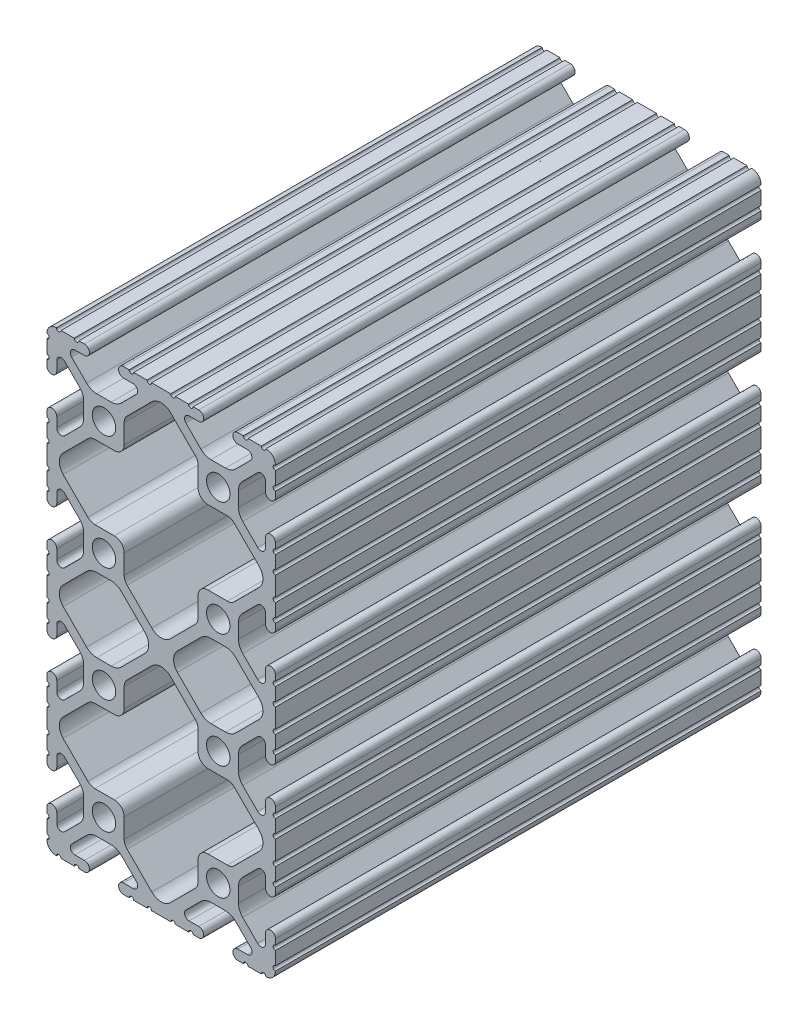
SolidWorks part; units mm, degrees
ref_plane "Front Plane" through (0, 0, 0) normal (0, 0, 1) x (1, 0, 0)
ref_plane "Top Plane" through (0, 0, 0) normal (0, 1, 0) x (1, 0, 0)
ref_plane "Right Plane" through (0, 0, 0) normal (1, 0, 0) x (0, 0, -1)
sketch "Sketch1" plane through (0, 0, 0) normal (0, 0, 1) x (1, 0, 0)
  line L0 (2.286, 55.2958) -> (-2.0184, 55.2958)
  line L1 (-3.5809, 55.943) -> (-9.0725, 61.4345)
  line L2 (-9.0725, 65.5655) -> (-3.5809, 71.057)
  line L3 (-2.0184, 71.7042) -> (2.286, 71.7042)
  line L4 (4.4958, 73.914) -> (4.4958, 78.2184)
  line L5 (5.143, 79.7809) -> (10.6345, 85.2725)
  line L6 (14.7655, 85.2725) -> (20.257, 79.7809)
  line L7 (20.9042, 78.2184) -> (20.9042, 73.914)
  line L8 (23.114, 71.7042) -> (27.4184, 71.7042)
  line L9 (28.9809, 71.057) -> (34.4725, 65.5655)
  line L10 (34.4725, 61.4345) -> (28.9809, 55.943)
  line L11 (27.4184, 55.2958) -> (23.114, 55.2958)
  line L12 (20.9042, 53.086) -> (20.9042, 48.7816)
  line L13 (20.257, 47.2191) -> (14.7655, 41.7275)
  line L14 (10.6345, 41.7275) -> (5.143, 47.2191)
  line L15 (4.4958, 48.7816) -> (4.4958, 53.086)
  line L16 (4.4958, 23.114) -> (4.4958, 27.4184)
  line L17 (5.143, 28.9809) -> (10.6345, 34.4725)
  line L18 (14.7655, 34.4725) -> (20.257, 28.9809)
  line L19 (20.9042, 27.4184) -> (20.9042, 23.114)
  line L20 (23.114, 20.9042) -> (27.4184, 20.9042)
  line L21 (28.9809, 20.257) -> (34.4725, 14.7655)
  line L22 (34.4725, 10.6345) -> (28.9809, 5.143)
  line L23 (27.4184, 4.4958) -> (23.114, 4.4958)
  line L24 (20.9042, 2.286) -> (20.9042, -2.0184)
  line L25 (20.257, -3.5809) -> (14.7655, -9.0725)
  line L26 (10.6345, -9.0725) -> (5.143, -3.5809)
  line L27 (4.4958, -2.0184) -> (4.4958, 2.286)
  line L28 (2.286, 4.4958) -> (-2.0184, 4.4958)
  line L29 (-3.5809, 5.143) -> (-9.0725, 10.6345)
  line L30 (-9.0725, 14.7655) -> (-3.5809, 20.257)
  line L31 (-2.0184, 20.9042) -> (2.286, 20.9042)
  line L32 (27.0186, 29.8958) -> (23.7824, 29.8958)
  line L33 (21.5373, 30.8258) -> (16.3286, 36.0346)
  line L34 (16.3286, 40.1654) -> (21.5373, 45.3742)
  line L35 (23.7824, 46.3042) -> (27.0186, 46.3042)
  line L36 (29.2636, 45.3743) -> (34.4725, 40.1655)
  line L37 (34.4725, 36.0345) -> (29.2636, 30.8257)
  line L38 (1.6176, 29.8958) -> (-1.6186, 29.8958)
  line L39 (-3.8636, 30.8257) -> (-9.0725, 36.0345)
  line L40 (-9.0725, 40.1655) -> (-3.8636, 45.3743)
  line L41 (-1.6186, 46.3042) -> (1.6176, 46.3042)
  line L42 (3.8627, 45.3742) -> (9.0714, 40.1654)
  line L43 (9.0714, 36.0346) -> (3.8627, 30.8258)
  line L44 (-12.7, 40.2336) -> (-12.7, 35.9664)
  line L45 (-12.7, 34.9504) -> (-12.7, 32.004)
  line L46 (-12.7, 30.988) -> (-12.7, 29.7434)
  line L47 (-10.4902, 29.7434) -> (-10.4902, 31.8743)
  line L48 (-8.7558, 32.5927) -> (-5.4258, 29.2627)
  line L49 (-4.4958, 27.0176) -> (-4.4958, 23.7824)
  line L50 (-5.4258, 21.5373) -> (-8.7558, 18.2073)
  line L51 (-10.4902, 18.9257) -> (-10.4902, 21.0566)
  line L52 (-12.7, 21.0566) -> (-12.7, 19.812)
  line L53 (-12.7, 18.796) -> (-12.7, 15.8496)
  line L54 (-12.7, 14.8336) -> (-12.7, 10.5664)
  line L55 (-12.7, 9.5504) -> (-12.7, 6.604)
  line L56 (-12.7, 5.588) -> (-12.7, 4.3434)
  line L57 (-10.4902, 4.3434) -> (-10.4902, 6.4743)
  line L58 (-8.7558, 7.1927) -> (-5.4258, 3.8627)
  line L59 (-4.4958, 1.6176) -> (-4.4958, -1.6176)
  line L60 (-5.4258, -3.8627) -> (-8.7558, -7.1927)
  line L61 (-10.4902, -6.4743) -> (-10.4902, -4.3434)
  line L62 (-12.7, -4.3434) -> (-12.7, -5.588)
  line L63 (-12.7, -6.604) -> (-12.7, -9.5504)
  line L64 (-9.5504, -12.7) -> (-6.604, -12.7)
  line L65 (-5.588, -12.7) -> (-4.3434, -12.7)
  line L66 (-4.3434, -10.4902) -> (-6.4743, -10.4902)
  line L67 (-7.1927, -8.7558) -> (-3.8627, -5.4258)
  line L68 (-1.6176, -4.4958) -> (1.6176, -4.4958)
  line L69 (3.8627, -5.4258) -> (7.1927, -8.7558)
  line L70 (6.4743, -10.4902) -> (4.3434, -10.4902)
  line L71 (4.3434, -12.7) -> (5.588, -12.7)
  line L72 (6.604, -12.7) -> (9.5504, -12.7)
  line L73 (10.5664, -12.7) -> (14.8336, -12.7)
  line L74 (15.8496, -12.7) -> (18.796, -12.7)
  line L75 (19.812, -12.7) -> (21.0566, -12.7)
  line L76 (21.0566, -10.4902) -> (18.9257, -10.4902)
  line L77 (18.2073, -8.7558) -> (21.5373, -5.4258)
  line L78 (23.7824, -4.4958) -> (27.0176, -4.4958)
  line L79 (29.2627, -5.4258) -> (32.5927, -8.7558)
  line L80 (31.8743, -10.4902) -> (29.7434, -10.4902)
  line L81 (29.7434, -12.7) -> (30.988, -12.7)
  line L82 (32.004, -12.7) -> (34.9504, -12.7)
  line L83 (38.1, -9.5504) -> (38.1, -6.604)
  line L84 (38.1, -5.588) -> (38.1, -4.3434)
  line L85 (35.8902, -4.3434) -> (35.8902, -6.4743)
  line L86 (34.1558, -7.1927) -> (30.8258, -3.8627)
  line L87 (29.8958, -1.6176) -> (29.8958, 1.6176)
  line L88 (30.8258, 3.8627) -> (34.1558, 7.1927)
  line L89 (35.8902, 6.4743) -> (35.8902, 4.3434)
  line L90 (38.1, 4.3434) -> (38.1, 5.588)
  line L91 (38.1, 6.604) -> (38.1, 9.5504)
  line L92 (38.1, 10.5664) -> (38.1, 14.8336)
  line L93 (38.1, 15.8496) -> (38.1, 18.796)
  line L94 (38.1, 19.812) -> (38.1, 21.0566)
  line L95 (35.8902, 21.0566) -> (35.8902, 18.9257)
  line L96 (34.1558, 18.2073) -> (30.8258, 21.5373)
  line L97 (29.8958, 23.7824) -> (29.8958, 27.0176)
  line L98 (30.8258, 29.2627) -> (34.1558, 32.5927)
  line L99 (35.8902, 31.8743) -> (35.8902, 29.7434)
  line L100 (38.1, 29.7434) -> (38.1, 30.988)
  line L101 (38.1, 32.004) -> (38.1, 34.9504)
  line L102 (38.1, 35.9664) -> (38.1, 40.2336)
  line L103 (38.1, 41.2496) -> (38.1, 44.196)
  line L104 (38.1, 45.212) -> (38.1, 46.4566)
  line L105 (35.8902, 46.4566) -> (35.8902, 44.3257)
  line L106 (34.1558, 43.6073) -> (30.8258, 46.9373)
  line L107 (29.8958, 49.1824) -> (29.8958, 52.4176)
  line L108 (30.8258, 54.6627) -> (34.1558, 57.9927)
  line L109 (35.8902, 57.2743) -> (35.8902, 55.1434)
  line L110 (38.1, 55.1434) -> (38.1, 56.388)
  line L111 (38.1, 57.404) -> (38.1, 60.3504)
  line L112 (38.1, 61.3664) -> (38.1, 65.6336)
  line L113 (38.1, 66.6496) -> (38.1, 69.596)
  line L114 (38.1, 70.612) -> (38.1, 71.8566)
  line L115 (35.8902, 71.8566) -> (35.8902, 69.7257)
  line L116 (34.1558, 69.0073) -> (30.8258, 72.3373)
  line L117 (29.8958, 74.5824) -> (29.8958, 77.8176)
  line L118 (30.8258, 80.0627) -> (34.1558, 83.3927)
  line L119 (35.8902, 82.6743) -> (35.8902, 80.5434)
  line L120 (38.1, 80.5434) -> (38.1, 81.788)
  line L121 (38.1, 82.804) -> (38.1, 85.7504)
  line L122 (34.9504, 88.9) -> (32.004, 88.9)
  line L123 (30.988, 88.9) -> (29.7434, 88.9)
  line L124 (29.7434, 86.6902) -> (31.8743, 86.6902)
  line L125 (32.5927, 84.9558) -> (29.2627, 81.6258)
  line L126 (27.0176, 80.6958) -> (23.7824, 80.6958)
  line L127 (21.5373, 81.6258) -> (18.2073, 84.9558)
  line L128 (18.9257, 86.6902) -> (21.0566, 86.6902)
  line L129 (21.0566, 88.9) -> (19.812, 88.9)
  line L130 (18.796, 88.9) -> (15.8496, 88.9)
  line L131 (14.8336, 88.9) -> (10.5664, 88.9)
  line L132 (9.5504, 88.9) -> (6.604, 88.9)
  line L133 (5.588, 88.9) -> (4.3434, 88.9)
  line L134 (4.3434, 86.6902) -> (6.4743, 86.6902)
  line L135 (7.1927, 84.9558) -> (3.8627, 81.6258)
  line L136 (1.6176, 80.6958) -> (-1.6176, 80.6958)
  line L137 (-3.8627, 81.6258) -> (-7.1927, 84.9558)
  line L138 (-6.4743, 86.6902) -> (-4.3434, 86.6902)
  line L139 (-4.3434, 88.9) -> (-5.588, 88.9)
  line L140 (-6.604, 88.9) -> (-9.5504, 88.9)
  line L141 (-12.7, 85.7504) -> (-12.7, 82.804)
  line L142 (-12.7, 81.788) -> (-12.7, 80.5434)
  line L143 (-10.4902, 80.5434) -> (-10.4902, 82.6743)
  line L144 (-8.7558, 83.3927) -> (-5.4258, 80.0627)
  line L145 (-4.4958, 77.8176) -> (-4.4958, 74.5824)
  line L146 (-5.4258, 72.3373) -> (-8.7558, 69.0073)
  line L147 (-10.4902, 69.7257) -> (-10.4902, 71.8566)
  line L148 (-12.7, 71.8566) -> (-12.7, 70.612)
  line L149 (-12.7, 69.596) -> (-12.7, 66.6496)
  line L150 (-12.7, 65.6336) -> (-12.7, 61.3664)
  line L151 (-12.7, 60.3504) -> (-12.7, 57.404)
  line L152 (-12.7, 56.388) -> (-12.7, 55.1434)
  line L153 (-10.4902, 55.1434) -> (-10.4902, 57.2743)
  line L154 (-8.7558, 57.9927) -> (-5.4258, 54.6627)
  line L155 (-4.4958, 52.4176) -> (-4.4958, 49.1824)
  line L156 (-5.4258, 46.9373) -> (-8.7558, 43.6073)
  line L157 (-10.4902, 44.3257) -> (-10.4902, 46.4566)
  line L158 (-12.7, 46.4566) -> (-12.7, 45.212)
  line L159 (-12.7, 44.196) -> (-12.7, 41.2496)
  arc A0 (4.4958, 53.086) -> (2.286, 55.2958) centre (2.286, 53.086) ccw
  arc A1 (-3.5809, 55.943) -> (-2.0184, 55.2958) centre (-2.0184, 57.5056) ccw
  arc A2 (-9.0725, 65.5655) -> (-9.0725, 61.4345) centre (-7.0071, 63.5) ccw
  arc A3 (-2.0184, 71.7042) -> (-3.5809, 71.057) centre (-2.0184, 69.4944) ccw
  arc A4 (2.286, 71.7042) -> (4.4958, 73.914) centre (2.286, 73.914) ccw
  arc A5 (5.143, 79.7809) -> (4.4958, 78.2184) centre (6.7056, 78.2184) ccw
  arc A6 (14.7655, 85.2725) -> (10.6345, 85.2725) centre (12.7, 83.2071) ccw
  arc A7 (20.9042, 78.2184) -> (20.257, 79.7809) centre (18.6944, 78.2184) ccw
  arc A8 (20.9042, 73.914) -> (23.114, 71.7042) centre (23.114, 73.914) ccw
  arc A9 (28.9809, 71.057) -> (27.4184, 71.7042) centre (27.4184, 69.4944) ccw
  arc A10 (34.4725, 61.4345) -> (34.4725, 65.5655) centre (32.4071, 63.5) ccw
  arc A11 (27.4184, 55.2958) -> (28.9809, 55.943) centre (27.4184, 57.5056) ccw
  arc A12 (23.114, 55.2958) -> (20.9042, 53.086) centre (23.114, 53.086) ccw
  arc A13 (20.257, 47.2191) -> (20.9042, 48.7816) centre (18.6944, 48.7816) ccw
  arc A14 (10.6345, 41.7275) -> (14.7655, 41.7275) centre (12.7, 43.7929) ccw
  arc A15 (4.4958, 48.7816) -> (5.143, 47.2191) centre (6.7056, 48.7816) ccw
  arc A16 (2.286, 20.9042) -> (4.4958, 23.114) centre (2.286, 23.114) ccw
  arc A17 (5.143, 28.9809) -> (4.4958, 27.4184) centre (6.7056, 27.4184) ccw
  arc A18 (14.7655, 34.4725) -> (10.6345, 34.4725) centre (12.7, 32.4071) ccw
  arc A19 (20.9042, 27.4184) -> (20.257, 28.9809) centre (18.6944, 27.4184) ccw
  arc A20 (20.9042, 23.114) -> (23.114, 20.9042) centre (23.114, 23.114) ccw
  arc A21 (28.9809, 20.257) -> (27.4184, 20.9042) centre (27.4184, 18.6944) ccw
  arc A22 (34.4725, 10.6345) -> (34.4725, 14.7655) centre (32.4071, 12.7) ccw
  arc A23 (27.4184, 4.4958) -> (28.9809, 5.143) centre (27.4184, 6.7056) ccw
  arc A24 (23.114, 4.4958) -> (20.9042, 2.286) centre (23.114, 2.286) ccw
  arc A25 (20.257, -3.5809) -> (20.9042, -2.0184) centre (18.6944, -2.0184) ccw
  arc A26 (10.6345, -9.0725) -> (14.7655, -9.0725) centre (12.7, -7.0071) ccw
  arc A27 (4.4958, -2.0184) -> (5.143, -3.5809) centre (6.7056, -2.0184) ccw
  arc A28 (4.4958, 2.286) -> (2.286, 4.4958) centre (2.286, 2.286) ccw
  arc A29 (-3.5809, 5.143) -> (-2.0184, 4.4958) centre (-2.0184, 6.7056) ccw
  arc A30 (-9.0725, 14.7655) -> (-9.0725, 10.6345) centre (-7.0071, 12.7) ccw
  arc A31 (-2.0184, 20.9042) -> (-3.5809, 20.257) centre (-2.0184, 18.6944) ccw
  arc A32 (27.0186, 29.8958) -> (29.2636, 30.8257) centre (27.0186, 33.0708) ccw
  arc A33 (21.5373, 30.8258) -> (23.7824, 29.8958) centre (23.7824, 33.0708) ccw
  arc A34 (16.3286, 40.1654) -> (16.3286, 36.0346) centre (18.3941, 38.1) ccw
  arc A35 (23.7824, 46.3042) -> (21.5373, 45.3742) centre (23.7824, 43.1292) ccw
  arc A36 (29.2636, 45.3743) -> (27.0186, 46.3042) centre (27.0186, 43.1292) ccw
  arc A37 (34.4725, 36.0345) -> (34.4725, 40.1655) centre (32.4071, 38.1) ccw
  arc A38 (1.6176, 29.8958) -> (3.8627, 30.8258) centre (1.6176, 33.0708) ccw
  arc A39 (-3.8636, 30.8257) -> (-1.6186, 29.8958) centre (-1.6186, 33.0708) ccw
  arc A40 (-9.0725, 40.1655) -> (-9.0725, 36.0345) centre (-7.0071, 38.1) ccw
  arc A41 (-1.6186, 46.3042) -> (-3.8636, 45.3743) centre (-1.6186, 43.1292) ccw
  arc A42 (3.8627, 45.3742) -> (1.6176, 46.3042) centre (1.6176, 43.1292) ccw
  arc A43 (9.0714, 36.0346) -> (9.0714, 40.1654) centre (7.0059, 38.1) ccw
  circle A44 centre (25.4, 76.2) radius 2.6035
  circle A45 centre (0, 76.2) radius 2.6035
  circle A46 centre (25.4, 50.8) radius 2.6035
  circle A47 centre (0, 50.8) radius 2.6035
  circle A48 centre (25.4, 0) radius 2.6035
  circle A49 centre (0, 0) radius 2.6035
  circle A50 centre (25.4, 25.4) radius 2.6035
  circle A51 centre (0, 25.4) radius 2.6035
  arc A52 (-12.7, 34.9504) -> (-12.7, 35.9664) centre (-12.7, 35.4584) ccw
  arc A53 (-12.7, 30.988) -> (-12.7, 32.004) centre (-12.7, 31.496) ccw
  arc A54 (-12.7, 29.7434) -> (-10.4902, 29.7434) centre (-11.5951, 29.7434) ccw
  arc A55 (-8.7558, 32.5927) -> (-10.4902, 31.8743) centre (-9.4742, 31.8743) ccw
  arc A56 (-4.4958, 27.0176) -> (-5.4258, 29.2627) centre (-7.6708, 27.0176) ccw
  arc A57 (-5.4258, 21.5373) -> (-4.4958, 23.7824) centre (-7.6708, 23.7824) ccw
  arc A58 (-10.4902, 18.9257) -> (-8.7558, 18.2073) centre (-9.4742, 18.9257) ccw
  arc A59 (-10.4902, 21.0566) -> (-12.7, 21.0566) centre (-11.5951, 21.0566) ccw
  arc A60 (-12.7, 18.796) -> (-12.7, 19.812) centre (-12.7, 19.304) ccw
  arc A61 (-12.7, 14.8336) -> (-12.7, 15.8496) centre (-12.7, 15.3416) ccw
  arc A62 (-12.7, 9.5504) -> (-12.7, 10.5664) centre (-12.7, 10.0584) ccw
  arc A63 (-12.7, 5.588) -> (-12.7, 6.604) centre (-12.7, 6.096) ccw
  arc A64 (-12.7, 4.3434) -> (-10.4902, 4.3434) centre (-11.5951, 4.3434) ccw
  arc A65 (-8.7558, 7.1927) -> (-10.4902, 6.4743) centre (-9.4742, 6.4743) ccw
  arc A66 (-4.4958, 1.6176) -> (-5.4258, 3.8627) centre (-7.6708, 1.6176) ccw
  arc A67 (-5.4258, -3.8627) -> (-4.4958, -1.6176) centre (-7.6708, -1.6176) ccw
  arc A68 (-10.4902, -6.4743) -> (-8.7558, -7.1927) centre (-9.4742, -6.4743) ccw
  arc A69 (-10.4902, -4.3434) -> (-12.7, -4.3434) centre (-11.5951, -4.3434) ccw
  arc A70 (-12.7, -6.604) -> (-12.7, -5.588) centre (-12.7, -6.096) ccw
  arc A71 (-12.6998, -10.5664) -> (-12.7, -9.5504) centre (-12.7, -10.0584) ccw
  arc A72 (-12.6998, -10.5664) -> (-10.5664, -12.6998) centre (-10.5918, -10.5918) ccw
  arc A73 (-9.5504, -12.7) -> (-10.5664, -12.6998) centre (-10.0584, -12.7) ccw
  arc A74 (-5.588, -12.7) -> (-6.604, -12.7) centre (-6.096, -12.7) ccw
  arc A75 (-4.3434, -12.7) -> (-4.3434, -10.4902) centre (-4.3434, -11.5951) ccw
  arc A76 (-7.1927, -8.7558) -> (-6.4743, -10.4902) centre (-6.4743, -9.4742) ccw
  arc A77 (-1.6176, -4.4958) -> (-3.8627, -5.4258) centre (-1.6176, -7.6708) ccw
  arc A78 (3.8627, -5.4258) -> (1.6176, -4.4958) centre (1.6176, -7.6708) ccw
  arc A79 (6.4743, -10.4902) -> (7.1927, -8.7558) centre (6.4743, -9.4742) ccw
  arc A80 (4.3434, -10.4902) -> (4.3434, -12.7) centre (4.3434, -11.5951) ccw
  arc A81 (6.604, -12.7) -> (5.588, -12.7) centre (6.096, -12.7) ccw
  arc A82 (10.5664, -12.7) -> (9.5504, -12.7) centre (10.0584, -12.7) ccw
  arc A83 (15.8496, -12.7) -> (14.8336, -12.7) centre (15.3416, -12.7) ccw
  arc A84 (19.812, -12.7) -> (18.796, -12.7) centre (19.304, -12.7) ccw
  arc A85 (21.0566, -12.7) -> (21.0566, -10.4902) centre (21.0566, -11.5951) ccw
  arc A86 (18.2073, -8.7558) -> (18.9257, -10.4902) centre (18.9257, -9.4742) ccw
  arc A87 (23.7824, -4.4958) -> (21.5373, -5.4258) centre (23.7824, -7.6708) ccw
  arc A88 (29.2627, -5.4258) -> (27.0176, -4.4958) centre (27.0176, -7.6708) ccw
  arc A89 (31.8743, -10.4902) -> (32.5927, -8.7558) centre (31.8743, -9.4742) ccw
  arc A90 (29.7434, -10.4902) -> (29.7434, -12.7) centre (29.7434, -11.5951) ccw
  arc A91 (32.004, -12.7) -> (30.988, -12.7) centre (31.496, -12.7) ccw
  arc A92 (35.9664, -12.6998) -> (34.9504, -12.7) centre (35.4584, -12.7) ccw
  arc A93 (35.9664, -12.6998) -> (38.0998, -10.5664) centre (35.9918, -10.5918) ccw
  arc A94 (38.1, -9.5504) -> (38.0998, -10.5664) centre (38.1, -10.0584) ccw
  arc A95 (38.1, -5.588) -> (38.1, -6.604) centre (38.1, -6.096) ccw
  arc A96 (38.1, -4.3434) -> (35.8902, -4.3434) centre (36.9951, -4.3434) ccw
  arc A97 (34.1558, -7.1927) -> (35.8902, -6.4743) centre (34.8742, -6.4743) ccw
  arc A98 (29.8958, -1.6176) -> (30.8258, -3.8627) centre (33.0708, -1.6176) ccw
  arc A99 (30.8258, 3.8627) -> (29.8958, 1.6176) centre (33.0708, 1.6176) ccw
  arc A100 (35.8902, 6.4743) -> (34.1558, 7.1927) centre (34.8742, 6.4743) ccw
  arc A101 (35.8902, 4.3434) -> (38.1, 4.3434) centre (36.9951, 4.3434) ccw
  arc A102 (38.1, 6.604) -> (38.1, 5.588) centre (38.1, 6.096) ccw
  arc A103 (38.1, 10.5664) -> (38.1, 9.5504) centre (38.1, 10.0584) ccw
  arc A104 (38.1, 15.8496) -> (38.1, 14.8336) centre (38.1, 15.3416) ccw
  arc A105 (38.1, 19.812) -> (38.1, 18.796) centre (38.1, 19.304) ccw
  arc A106 (38.1, 21.0566) -> (35.8902, 21.0566) centre (36.9951, 21.0566) ccw
  arc A107 (34.1558, 18.2073) -> (35.8902, 18.9257) centre (34.8742, 18.9257) ccw
  arc A108 (29.8958, 23.7824) -> (30.8258, 21.5373) centre (33.0708, 23.7824) ccw
  arc A109 (30.8258, 29.2627) -> (29.8958, 27.0176) centre (33.0708, 27.0176) ccw
  arc A110 (35.8902, 31.8743) -> (34.1558, 32.5927) centre (34.8742, 31.8743) ccw
  arc A111 (35.8902, 29.7434) -> (38.1, 29.7434) centre (36.9951, 29.7434) ccw
  arc A112 (38.1, 32.004) -> (38.1, 30.988) centre (38.1, 31.496) ccw
  arc A113 (38.1, 35.9664) -> (38.1, 34.9504) centre (38.1, 35.4584) ccw
  arc A114 (38.1, 41.2496) -> (38.1, 40.2336) centre (38.1, 40.7416) ccw
  arc A115 (38.1, 45.212) -> (38.1, 44.196) centre (38.1, 44.704) ccw
  arc A116 (38.1, 46.4566) -> (35.8902, 46.4566) centre (36.9951, 46.4566) ccw
  arc A117 (34.1558, 43.6073) -> (35.8902, 44.3257) centre (34.8742, 44.3257) ccw
  arc A118 (29.8958, 49.1824) -> (30.8258, 46.9373) centre (33.0708, 49.1824) ccw
  arc A119 (30.8258, 54.6627) -> (29.8958, 52.4176) centre (33.0708, 52.4176) ccw
  arc A120 (35.8902, 57.2743) -> (34.1558, 57.9927) centre (34.8742, 57.2743) ccw
  arc A121 (35.8902, 55.1434) -> (38.1, 55.1434) centre (36.9951, 55.1434) ccw
  arc A122 (38.1, 57.404) -> (38.1, 56.388) centre (38.1, 56.896) ccw
  arc A123 (38.1, 61.3664) -> (38.1, 60.3504) centre (38.1, 60.8584) ccw
  arc A124 (38.1, 66.6496) -> (38.1, 65.6336) centre (38.1, 66.1416) ccw
  arc A125 (38.1, 70.612) -> (38.1, 69.596) centre (38.1, 70.104) ccw
  arc A126 (38.1, 71.8566) -> (35.8902, 71.8566) centre (36.9951, 71.8566) ccw
  arc A127 (34.1558, 69.0073) -> (35.8902, 69.7257) centre (34.8742, 69.7257) ccw
  arc A128 (29.8958, 74.5824) -> (30.8258, 72.3373) centre (33.0708, 74.5824) ccw
  arc A129 (30.8258, 80.0627) -> (29.8958, 77.8176) centre (33.0708, 77.8176) ccw
  arc A130 (35.8902, 82.6743) -> (34.1558, 83.3927) centre (34.8742, 82.6743) ccw
  arc A131 (35.8902, 80.5434) -> (38.1, 80.5434) centre (36.9951, 80.5434) ccw
  arc A132 (38.1, 82.804) -> (38.1, 81.788) centre (38.1, 82.296) ccw
  arc A133 (38.0998, 86.7664) -> (38.1, 85.7504) centre (38.1, 86.2584) ccw
  arc A134 (38.0998, 86.7664) -> (35.9664, 88.8998) centre (35.9918, 86.7918) ccw
  arc A135 (34.9504, 88.9) -> (35.9664, 88.8998) centre (35.4584, 88.9) ccw
  arc A136 (30.988, 88.9) -> (32.004, 88.9) centre (31.496, 88.9) ccw
  arc A137 (29.7434, 88.9) -> (29.7434, 86.6902) centre (29.7434, 87.7951) ccw
  arc A138 (32.5927, 84.9558) -> (31.8743, 86.6902) centre (31.8743, 85.6742) ccw
  arc A139 (27.0176, 80.6958) -> (29.2627, 81.6258) centre (27.0176, 83.8708) ccw
  arc A140 (21.5373, 81.6258) -> (23.7824, 80.6958) centre (23.7824, 83.8708) ccw
  arc A141 (18.9257, 86.6902) -> (18.2073, 84.9558) centre (18.9257, 85.6742) ccw
  arc A142 (21.0566, 86.6902) -> (21.0566, 88.9) centre (21.0566, 87.7951) ccw
  arc A143 (18.796, 88.9) -> (19.812, 88.9) centre (19.304, 88.9) ccw
  arc A144 (14.8336, 88.9) -> (15.8496, 88.9) centre (15.3416, 88.9) ccw
  arc A145 (9.5504, 88.9) -> (10.5664, 88.9) centre (10.0584, 88.9) ccw
  arc A146 (5.588, 88.9) -> (6.604, 88.9) centre (6.096, 88.9) ccw
  arc A147 (4.3434, 88.9) -> (4.3434, 86.6902) centre (4.3434, 87.7951) ccw
  arc A148 (7.1927, 84.9558) -> (6.4743, 86.6902) centre (6.4743, 85.6742) ccw
  arc A149 (1.6176, 80.6958) -> (3.8627, 81.6258) centre (1.6176, 83.8708) ccw
  arc A150 (-3.8627, 81.6258) -> (-1.6176, 80.6958) centre (-1.6176, 83.8708) ccw
  arc A151 (-6.4743, 86.6902) -> (-7.1927, 84.9558) centre (-6.4743, 85.6742) ccw
  arc A152 (-4.3434, 86.6902) -> (-4.3434, 88.9) centre (-4.3434, 87.7951) ccw
  arc A153 (-6.604, 88.9) -> (-5.588, 88.9) centre (-6.096, 88.9) ccw
  arc A154 (-10.5664, 88.8998) -> (-9.5504, 88.9) centre (-10.0584, 88.9) ccw
  arc A155 (-10.5664, 88.8998) -> (-12.6998, 86.7664) centre (-10.5918, 86.7918) ccw
  arc A156 (-12.7, 85.7504) -> (-12.6998, 86.7664) centre (-12.7, 86.2584) ccw
  arc A157 (-12.7, 81.788) -> (-12.7, 82.804) centre (-12.7, 82.296) ccw
  arc A158 (-12.7, 80.5434) -> (-10.4902, 80.5434) centre (-11.5951, 80.5434) ccw
  arc A159 (-8.7558, 83.3927) -> (-10.4902, 82.6743) centre (-9.4742, 82.6743) ccw
  arc A160 (-4.4958, 77.8176) -> (-5.4258, 80.0627) centre (-7.6708, 77.8176) ccw
  arc A161 (-5.4258, 72.3373) -> (-4.4958, 74.5824) centre (-7.6708, 74.5824) ccw
  arc A162 (-10.4902, 69.7257) -> (-8.7558, 69.0073) centre (-9.4742, 69.7257) ccw
  arc A163 (-10.4902, 71.8566) -> (-12.7, 71.8566) centre (-11.5951, 71.8566) ccw
  arc A164 (-12.7, 69.596) -> (-12.7, 70.612) centre (-12.7, 70.104) ccw
  arc A165 (-12.7, 65.6336) -> (-12.7, 66.6496) centre (-12.7, 66.1416) ccw
  arc A166 (-12.7, 60.3504) -> (-12.7, 61.3664) centre (-12.7, 60.8584) ccw
  arc A167 (-12.7, 56.388) -> (-12.7, 57.404) centre (-12.7, 56.896) ccw
  arc A168 (-12.7, 55.1434) -> (-10.4902, 55.1434) centre (-11.5951, 55.1434) ccw
  arc A169 (-8.7558, 57.9927) -> (-10.4902, 57.2743) centre (-9.4742, 57.2743) ccw
  arc A170 (-4.4958, 52.4176) -> (-5.4258, 54.6627) centre (-7.6708, 52.4176) ccw
  arc A171 (-5.4258, 46.9373) -> (-4.4958, 49.1824) centre (-7.6708, 49.1824) ccw
  arc A172 (-10.4902, 44.3257) -> (-8.7558, 43.6073) centre (-9.4742, 44.3257) ccw
  arc A173 (-10.4902, 46.4566) -> (-12.7, 46.4566) centre (-11.5951, 46.4566) ccw
  arc A174 (-12.7, 44.196) -> (-12.7, 45.212) centre (-12.7, 44.704) ccw
  arc A175 (-12.7, 40.2336) -> (-12.7, 41.2496) centre (-12.7, 40.7416) ccw
extrude "Extrude1" add sketch "Sketch1" against normal blind 107.95
